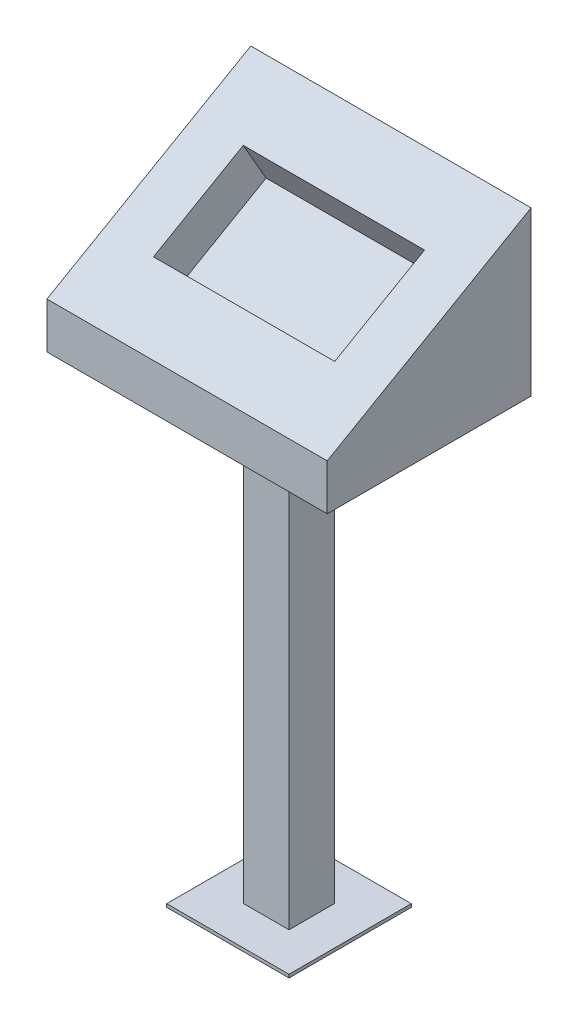
SolidWorks part; units mm, degrees
ref_plane "Alzado" through (0, 0, 0) normal (0, 0, 1) x (1, 0, 0)
ref_plane "Planta" through (0, 0, 0) normal (0, 1, 0) x (1, 0, 0)
ref_plane "Vista lateral" through (0, 0, 0) normal (1, 0, 0) x (0, 0, -1)
sketch "Croquis1" plane through (0, 0, 0) normal (0, 1, 0) x (1, 0, 0)
  line L1 (0, 0) -> (240, 0)
  line L2 (0, 0) -> (0, 240)
  line L3 (0, 240) -> (240, 240)
  line L4 (240, 0) -> (240, 240)
  dimension "D1" = 240
  dimension "D2" = 240
extrude "Saliente-Extruir1" add sketch "Croquis1" along normal blind 6.35
sketch "Croquis2" plane through (0, 6.35, 0) normal (0, 1, 0) x (1, 0, 0)
  line L0 (120, 240) -> (120, 0) construction
  line L1 (240, 240) -> (0, 240) construction
  line L2 (0, 0) -> (240, 0) construction
  line L4 (164.45, 75.55) -> (75.55, 75.55)
  line L5 (164.45, 75.55) -> (164.45, 164.45)
  line L6 (164.45, 164.45) -> (75.55, 164.45)
  line L7 (75.55, 75.55) -> (75.55, 164.45)
  line L8 (164.45, 75.55) -> (75.55, 164.45) construction
  line L9 (164.45, 164.45) -> (75.55, 75.55) construction
  point P6 (120, 120)
  dimension "D1" = 88.9
  dimension "D2" = 88.9
extrude "Saliente-Extruir2" add sketch "Croquis2" along normal blind 900
sketch "Croquis3" plane through (0, 906.35, 0) normal (0, 1, 0) x (1, 0, 0)
  line L0 (120, 164.45) -> (120, 75.55) construction
  line L1 (164.45, 164.45) -> (75.55, 164.45) construction
  line L2 (75.55, 75.55) -> (164.45, 75.55) construction
  line L4 (-155, -80) -> (395, -80)
  line L5 (-155, -80) -> (-155, 320)
  line L6 (-155, 320) -> (395, 320)
  line L7 (395, -80) -> (395, 320)
  line L8 (-155, -80) -> (395, 320) construction
  line L9 (-155, 320) -> (395, -80) construction
  point P6 (120, 120)
  dimension "D1" = 400
  dimension "D2" = 550
extrude "Saliente-Extruir3" add sketch "Croquis3" along normal blind 320
sketch "Croquis4" plane through (-155, 0, 0) normal (-1, 0, 0) x (0, 0, 1)
  line L0 (-320, 1226.35) -> (80, 996.35)
  line L1 (80, 1226.35) -> (80, 906.35) construction
  line L2 (-320, 1226.35) -> (80, 1226.35)
  line L3 (80, 1226.35) -> (80, 996.35)
  dimension "D1" = 90
extrude "Cortar-Extruir1" cut sketch "Croquis4" against normal up to surface (550 mm away) up to face at (395, 1066.35, -120)
sketch "Croquis6" plane through (0, 783.3537, 450.4284) normal (0, 0.8669, 0.4985) x (1, 0, 0)
  line L0 (120, 888.7101) -> (120, 427.2992) construction
  line L1 (395, 888.7101) -> (-155, 888.7101) construction
  line L2 (395, 427.2992) -> (-155, 427.2992) construction
  line L4 (-57.8, 556.4046) -> (297.8, 556.4046)
  line L5 (-57.8, 556.4046) -> (-57.8, 759.6046)
  line L6 (-57.8, 759.6046) -> (297.8, 759.6046)
  line L7 (297.8, 556.4046) -> (297.8, 759.6046)
  line L8 (-57.8, 556.4046) -> (297.8, 759.6046) construction
  line L9 (-57.8, 759.6046) -> (297.8, 556.4046) construction
  point P6 (120, 658.0046)
  dimension "D1" = 355.6
  dimension "D2" = 203.2
extrude "Cortar-Extruir2" cut sketch "Croquis6" against normal blind 90
